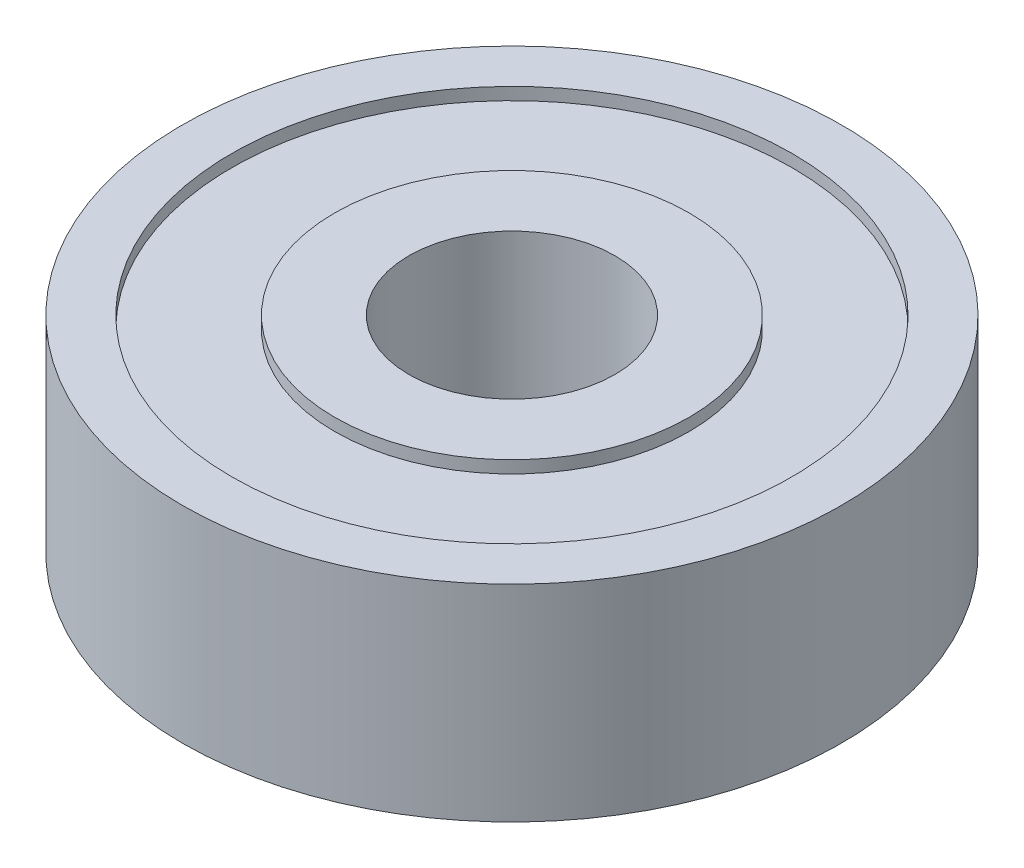
SolidWorks part; units mm, degrees
ref_plane "Front Plane" through (0, 0, 0) normal (0, 0, 1) x (1, 0, 0)
ref_plane "Top Plane" through (0, 0, 0) normal (0, 1, 0) x (1, 0, 0)
ref_plane "Right Plane" through (0, 0, 0) normal (1, 0, 0) x (0, 0, -1)
sketch "Sketch1" plane through (0, 0, 0) normal (1, 0, 0) x (0, 0, -1)
  line L0 (0, 4.825) -> (0, -4.825) construction
  line L1 (6.8, 2.5) -> (8, 2.5)
  line L2 (2.5, 2.5) -> (4.3, 2.5)
  line L3 (2.5, 2.5) -> (2.5, -2.5)
  line L4 (2.5, -2.5) -> (4.3, -2.5)
  line L5 (8, 2.5) -> (8, -2.5)
  line L6 (2.5, 2.5) -> (8, -2.5) construction
  line L7 (2.5, -2.5) -> (8, 2.5) construction
  line L9 (4.3, 2.5) -> (4.3, 2.2)
  line L10 (4.3, 2.2) -> (6.8, 2.2)
  line L11 (6.8, 2.5) -> (6.8, 2.2)
  line L13 (4.3, -2.5) -> (4.3, -2.2)
  line L14 (4.3, -2.2) -> (6.8, -2.2)
  line L15 (6.8, -2.5) -> (6.8, -2.2)
  line L16 (6.8, -2.5) -> (8, -2.5)
  point P0 (5.25, 0)
  point P4 (0, 0)
  dimension "D1" = 1.8
  dimension "D2" = 1.2
  dimension "D3" = 2.5
  dimension "D4" = 1.8
  dimension "D5" = 1.2
  dimension "D6" = 0.3
  dimension "D7" = 0.3
  dimension "D8" = 5
  dimension "D9" = 2.5
revolve "Revolve1" add sketch "Sketch1" angle 360 about L0
